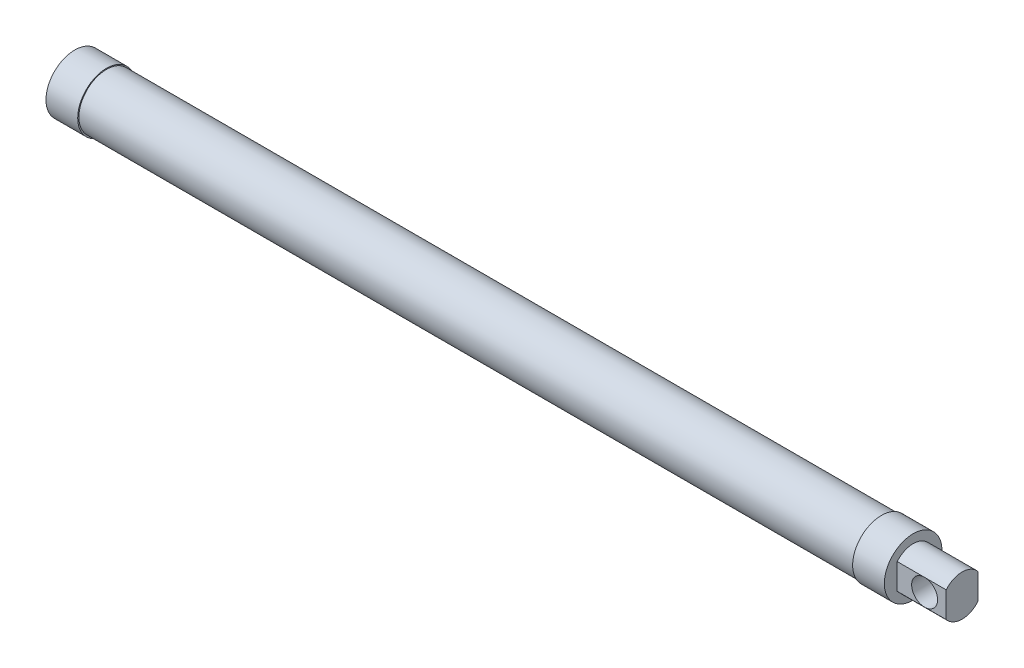
SolidWorks part; units mm, degrees
ref_plane "Front Plane" through (0, 0, 0) normal (0, 0, 1) x (1, 0, 0)
ref_plane "Top Plane" through (0, 0, 0) normal (0, 1, 0) x (1, 0, 0)
ref_plane "Right Plane" through (0, 0, 0) normal (1, 0, 0) x (0, 0, -1)
sketch "Sketch1" plane through (0, 0, 0) normal (0, 0, 1) x (1, 0, 0)
  line L1 (-119.8127, 3.4358) -> (160.1873, 3.4358)
  line L2 (-119.8127, 3.4358) -> (-119.8127, -6.1442)
  line L3 (-119.8127, -6.1442) -> (160.1873, -6.1442)
  line L4 (160.1873, 3.4358) -> (160.1873, -6.1442)
  dimension "D1" = 280
  dimension "D2" = 9.58
revolve "Revolve2" add sketch "Sketch1" angle 360 about L1
sketch "Sketch2" plane through (-119.8127, 0, 0) normal (-1, 0, 0) x (0, 0, 1)
  circle A0 centre (0, 3.4358) radius 3.05
  dimension "D1" = 6.1
extrude "Cut-Extrude1" cut sketch "Sketch2" against normal through all both and the other way through all
sketch "Sketch4" plane through (160.1873, 0, 0) normal (1, 0, 0) x (0, 0, -1)
  circle A0 centre (0, 3.4358) radius 10
  dimension "D1" = 20
extrude "Boss-Extrude1" add sketch "Sketch4" against normal blind 11
sketch "Sketch7" plane through (160.1873, 0, 0) normal (1, 0, 0) x (0, 0, -1)
  circle A0 centre (0, 3.3606) radius 3.05
  dimension "D1" = 6.1
extrude "Cut-Extrude2" cut sketch "Sketch7" against normal through all both and the other way through all
sketch "Sketch11" plane through (-119.8127, 0, 0) normal (-1, 0, 0) x (0, 0, 1)
  circle A0 centre (0, 3.3606) radius 10
  dimension "D1" = 20
extrude "Boss-Extrude2" add sketch "Sketch11" along normal blind 11 contours A0
sketch "Sketch12" plane through (-130.8127, 0, 0) normal (-1, 0, 0) x (0, 0, 1)
  circle A0 centre (0, 3.3362) radius 3.05
  dimension "D1" = 6.1
extrude "Cut-Extrude4" cut sketch "Sketch12" against normal through all both and the other way through all
sketch "Sketch13" plane through (160.1873, 0, 0) normal (1, 0, 0) x (0, 0, -1)
  circle A0 centre (0, 3.3362) radius 7.1
  dimension "D1" = 14.2
extrude "Boss-Extrude3" add sketch "Sketch13" along normal blind 17
sketch "Sketch14" plane through (0, 0, 0) normal (0, 0, 1) x (1, 0, 0)
  line L0 (177.1873, -3.7638) -> (177.1873, 10.4362) construction
  circle A0 centre (169.6873, 3.3362) radius 4.5
  dimension "D2" = 9
  dimension "D1" = 7.5
extrude "Cut-Extrude5" cut sketch "Sketch14" against normal through all both and the other way through all contours A0
sketch "Sketch16" plane through (177.1873, 0, 0) normal (1, 0, 0) x (0, 0, -1)
  line L0 (0, 3.3362) -> (-5.5154, 7.8072) construction
  line L1 (-5.5154, 7.8072) -> (-5.5154, -1.1348) construction
  line L2 (-5.5154, -1.1348) -> (5.5154, -1.1348) construction
  line L3 (5.5154, -1.1348) -> (5.5154, 7.8072) construction
  line L4 (5.5154, 7.8072) -> (-5.5154, 7.8072) construction
  line L6 (-5.5154, 7.8072) -> (-10.6342, 7.8072)
  line L7 (-5.5154, 7.8072) -> (-5.5154, -3.1164)
  line L8 (-5.5154, -3.1164) -> (-10.6342, -3.1164)
  line L9 (-10.6342, 7.8072) -> (-10.6342, -3.1164)
  line L10 (5.5154, 7.8072) -> (12.9279, 7.8072)
  line L11 (5.5154, 7.8072) -> (5.5154, -3.1164)
  line L12 (5.5154, -3.1164) -> (12.9279, -3.1164)
  line L13 (12.9279, 7.8072) -> (12.9279, -3.1164)
  circle A0 centre (0, 3.3362) radius 7.1 construction
  circle A1 centre (0, 3.3362) radius 7.1 construction
extrude "Cut-Extrude6" cut sketch "Sketch16" against normal up to surface (17 mm away) up to face at (160.1873, 3.3362, -7.1)
